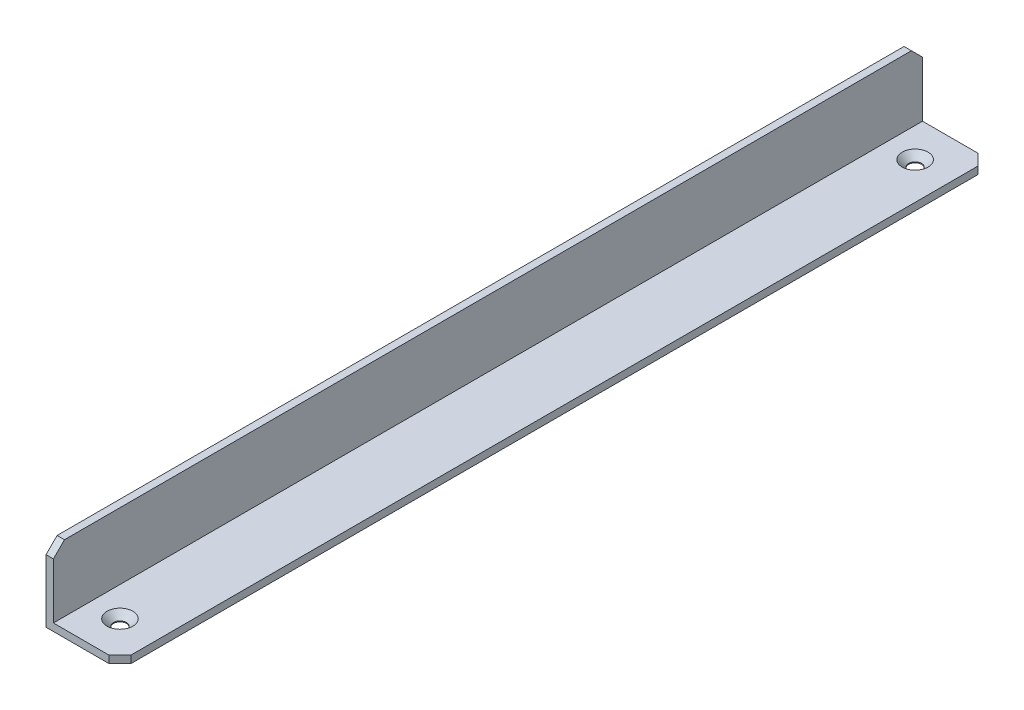
SolidWorks part; units mm, degrees
material "Aluminium"
ref_plane "Front Plane" through (0, 0, 0) normal (0, 0, 1) x (1, 0, 0)
ref_plane "Top Plane" through (0, 0, 0) normal (0, 1, 0) x (1, 0, 0)
ref_plane "Right Plane" through (0, 0, 0) normal (1, 0, 0) x (0, 0, -1)
sketch "Sketch1" plane through (0, 0, 0) normal (0, 0, 1) x (1, 0, 0)
  line L1 (0, 0) -> (20, 0)
  line L2 (0, 0) -> (0, 20)
  line L3 (0, 20) -> (2, 20)
  line L4 (20, 0) -> (20, 2)
  line L7 (20, 2) -> (2, 2)
  line L8 (2, 20) -> (2, 2)
  dimension "D1" = 20
  dimension "D2" = 2
extrude "Boss-Extrude1" add sketch "Sketch1" along normal mid plane 235
sketch "Sketch2" plane through (0, 2, 0) normal (0, 1, 0) x (1, 0, 0)
  line L0 (10, -107.5) -> (10, -117.5) construction
  line L2 (10, 117.5) -> (10, 107.5) construction
  line L4 (0, -117.5) -> (0, 117.5) construction
  line L5 (20, -117.5) -> (2, -117.5) construction
  line L6 (20, 117.5) -> (2, 117.5) construction
  circle A0 centre (10, 107.5) radius 3.5
  circle A1 centre (10, -107.5) radius 3.5
  dimension "D1" = 10
  dimension "D2" = 7
  dimension "D3" = 10
extrude "Cut-Extrude1" cut sketch "Sketch2" against normal blind 450 draft 45
sketch "Sketch3" plane through (0, 2, 0) normal (0, 1, 0) x (1, 0, 0)
  circle A0 centre (10, -107.5) radius 1.75
  circle A1 centre (10, 107.5) radius 1.75
  dimension "D1" = 3.5
extrude "Cut-Extrude2" cut sketch "Sketch3" against normal through all
ref_plane "Plane1" through (0, 0, 0) normal (0.7071, -0.7071, 0) x (0, 0, -1)
mirror "Mirror1" [suppressed] about plane through (0, 0, 0) normal (0.7071, -0.7071, 0)
chamfer "Chamfer1" distance 3 angle 45 4 edges at (20, 1, -117.5) (1, 20, -117.5) (20, 1, 117.5) (1, 20, 117.5)
